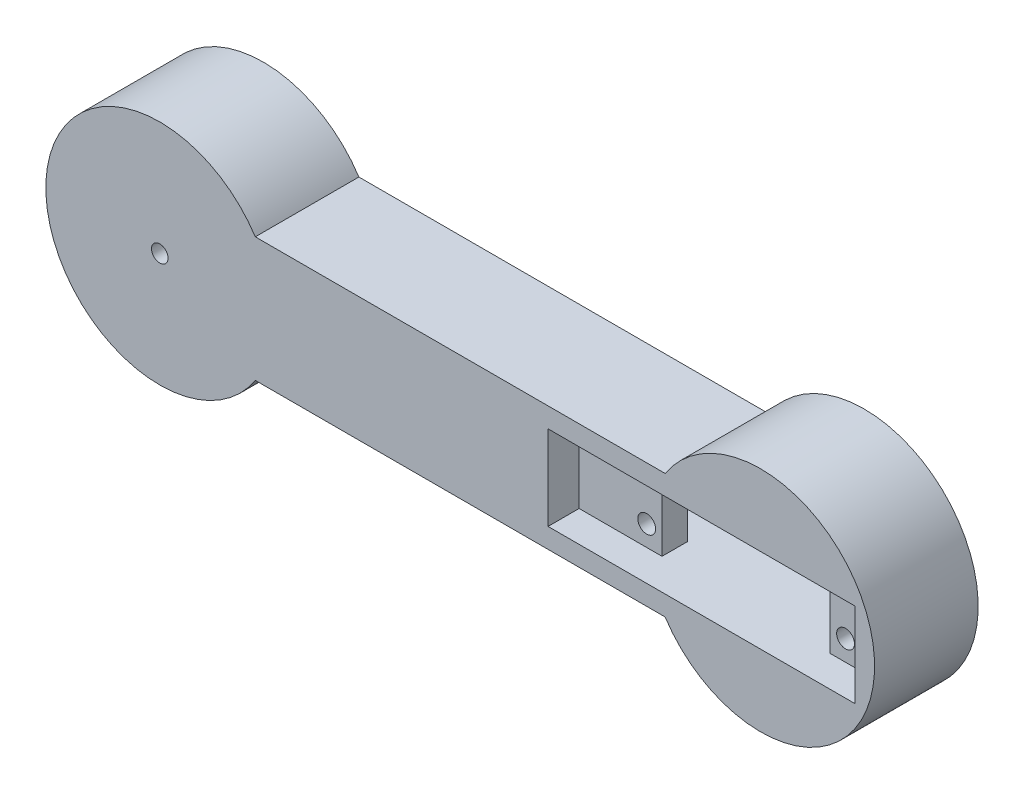
SolidWorks part; units mm, degrees
material "Custom Plastic"
ref_plane "Front Plane" through (0, 0, 0) normal (0, 0, 1) x (1, 0, 0)
ref_plane "Top Plane" through (0, 0, 0) normal (0, 1, 0) x (1, 0, 0)
ref_plane "Right Plane" through (0, 0, 0) normal (1, 0, 0) x (0, 0, -1)
sketch "Sketch1" plane through (0, 0, 0) normal (0, 0, 1) x (1, 0, 0)
  line L1 (0, 15) -> (145, 15)
  line L2 (0, 15) -> (0, -15)
  line L3 (0, -15) -> (145, -15)
  line L4 (145, 15) -> (145, -15)
  circle A0 centre (0, 0) radius 27.5
  circle A1 centre (145, 0) radius 27.5
  circle A2 centre (0, 0) radius 20
  point P9 (0, 0)
  dimension "D1" = 55
  dimension "D4" = 55
  dimension "D5" = 40
  dimension "D2" = 145
  dimension "D3" = 30
extrude "Boss-Extrude1" add sketch "Sketch1" along normal blind 25 contours L3 A1 L1 L4 | A1 L1 A0 L3 | L1 A1 L3 L4 | A2 L3 A0 L1 | A2 L1 A0 L3 | L3 A2 L1 L2 | L1 A2 L3 L2
sketch "Sketch19" plane through (0, 0, 0) normal (0, 0, -1) x (-1, 0, 0)
  circle A0 centre (0, 0) radius 20
extrude "Cut-Extrude14" cut sketch "Sketch19" against normal blind 5 contours A0
sketch "Sketch22" plane through (0, 0, 25) normal (0, 0, 1) x (1, 0, 0)
  circle A0 centre (0, 0) radius 2
  arc A4 (23.0489, 15) -> (23.0489, -15) centre (0, 0) ccw construction
  dimension "D1" = 4
extrude "Cut-Extrude17" cut sketch "Sketch22" against normal up to surface (20 mm away) up to face at (-20, 0, 5)
sketch "Sketch23" plane through (0, 0, 0) normal (0, 0, -1) x (-1, 0, 0)
  line L1 (-106.75, 10.2) -> (-161.25, 10.2)
  line L2 (-106.75, 10.2) -> (-106.75, -10.2)
  line L3 (-106.75, -10.2) -> (-161.25, -10.2)
  line L4 (-161.25, 10.2) -> (-161.25, -10.2)
  line L6 (-107, 0) -> (-106.75, 0)
  line L7 (-43.5913, 98.8265) -> (-45.7768, 103.29) construction
  line L8 (-161, 0) -> (-161.25, 0)
  line L10 (-87.2412, 114.1536) -> (-89.4267, 118.6171) construction
  line L11 (-154, 0) -> (-154.3, 0) construction
  line L12 (-154.3, -10.2) -> (-113.7, -10.2)
  line L13 (-154.3, -10.2) -> (-154.3, 10.2)
  line L14 (-154.3, 10.2) -> (-113.7, 10.2)
  line L15 (-113.7, -10.2) -> (-113.7, 10.2)
  line L16 (-76.072, 114.1775) -> (-81.7487, 125.7711) construction
  line L17 (-114, 0) -> (-113.7, 0) construction
  line L18 (-43.7388, 102.8241) -> (-49.4154, 114.4177) construction
  dimension "D1" = 54.5
  dimension "D2" = 40.6
  dimension "D3" = 20.4
extrude "Cut-Extrude18" cut sketch "Sketch23" against normal blind 11.3
sketch "Sketch24" plane through (0, 0, 11.3) normal (0, 0, -1) x (-1, 0, 0)
  line L0 (-106.75, -10.2) -> (-161.25, -10.2) construction
  line L1 (-154.3, -10.2) -> (-113.7, -10.2)
  line L2 (-154.3, -10.2) -> (-154.3, 10.2)
  line L3 (-154.3, 10.2) -> (-113.7, 10.2)
  line L4 (-113.7, -10.2) -> (-113.7, 10.2)
  line L5 (-106.75, 10.2) -> (-161.25, 10.2) construction
  line L6 (-161.25, -0.6275) -> (-154.3, -0.6275)
  line L7 (-161.25, 10.2) -> (-161.25, -10.2) construction
  line L8 (-113.7, 170.6482) -> (-106.75, 170.6482)
  line L9 (-49.2848, 103.6112) -> (-47.2294, 101.472) construction
  line L10 (-106.75, 10.2) -> (-106.75, -10.2) construction
  line M7 (-161.25, -10.2) -> (-106.75, -10.2)
  line M9 (-106.75, 10.2) -> (-161.25, 10.2)
  dimension "D1" = 40.6
extrude "Cut-Extrude19" cut sketch "Sketch24" against normal up to surface (13.7 mm away) contours L4 L2 M7 M9 up to face at (2, 0, 25)
sketch "Sketch25" plane through (154.3, 0, 0) normal (-1, 0, 0) x (0, 0, 1)
  line L0 (25, -27.5) -> (25, 27.5) construction
  line L1 (25, 12) -> (17.5, 12)
  line L2 (25, 12) -> (25, -12)
  line L3 (25, -12) -> (17.5, -12)
  line L4 (17.5, 12) -> (17.5, -12)
  line L5 (12.5, 27.5) -> (12.5, 12)
  line L6 (25, 27.5) -> (0, 27.5) construction
  line L7 (12.5, -12) -> (12.5, -27.5)
  line L8 (0, -27.5) -> (25, -27.5) construction
  line M5 (25, -10.2) -> (25, 10.2)
  line M6 (25, 10.2) -> (11.3, 10.2)
  line M8 (11.3, -10.2) -> (25, -10.2)
  dimension "D1" = 24
  dimension "D2" = 7.5
extrude "Cut-Extrude20" cut sketch "Sketch25" against normal blind 13.5 contours L4 M6 M8 M5
sketch "Sketch26" plane through (113.7, 0, 0) normal (1, 0, 0) x (0, 0, -1)
  line L0 (-16.9501, -10.2) -> (-16.9501, -27.5)
  line L1 (-25, -10.2) -> (-17.5, -10.2)
  line L2 (-25, -10.2) -> (-25, 10.2)
  line L3 (-25, 10.2) -> (-17.5, 10.2)
  line L4 (-17.5, -10.2) -> (-17.5, 10.2)
  line L5 (-25, -27.5) -> (0, -27.5) construction
  line L6 (-21.25, 10.2) -> (-21.25, 27.5)
  line L7 (0, 27.5) -> (-25, 27.5) construction
  line M5 (-25, -10.2) -> (-11.3, -10.2)
  line M7 (-11.3, 10.2) -> (-25, 10.2)
  line M8 (-25, 10.2) -> (-25, -10.2)
  dimension "D1" = 7.5
extrude "Cut-Extrude21" cut sketch "Sketch26" against normal blind 20 contours L4 L3 M5 M7 M8
sketch "Sketch27" plane through (0, 0, 11.3) normal (0, 0, -1) x (-1, 0, 0)
  line L0 (-161.25, -5.25) -> (-158, -5.25)
  line L1 (-161.25, 10.2) -> (-161.25, -10.2) construction
  line L3 (-158, -5.25) -> (-110, -5.25)
  line L4 (-158, -5.25) -> (-158, 5.25)
  line L5 (-158, 5.25) -> (-110, 5.25)
  line L6 (-110, -5.25) -> (-110, 5.25)
  circle A0 centre (-110, -5.25) radius 2.15
  circle A1 centre (-110, 5.25) radius 2.15
  circle A2 centre (-158, 5.25) radius 2.15
  circle A3 centre (-158, -5.25) radius 2.15
  dimension "D1" = 4.3
extrude "Cut-Extrude22" cut sketch "Sketch27" against normal blind 12 contours L6 A1 L5 | L5 A1 L6 | L6 A0 L3 | L3 A0 L6 | L4 A2 L5 | L5 A2 L4 | A3
